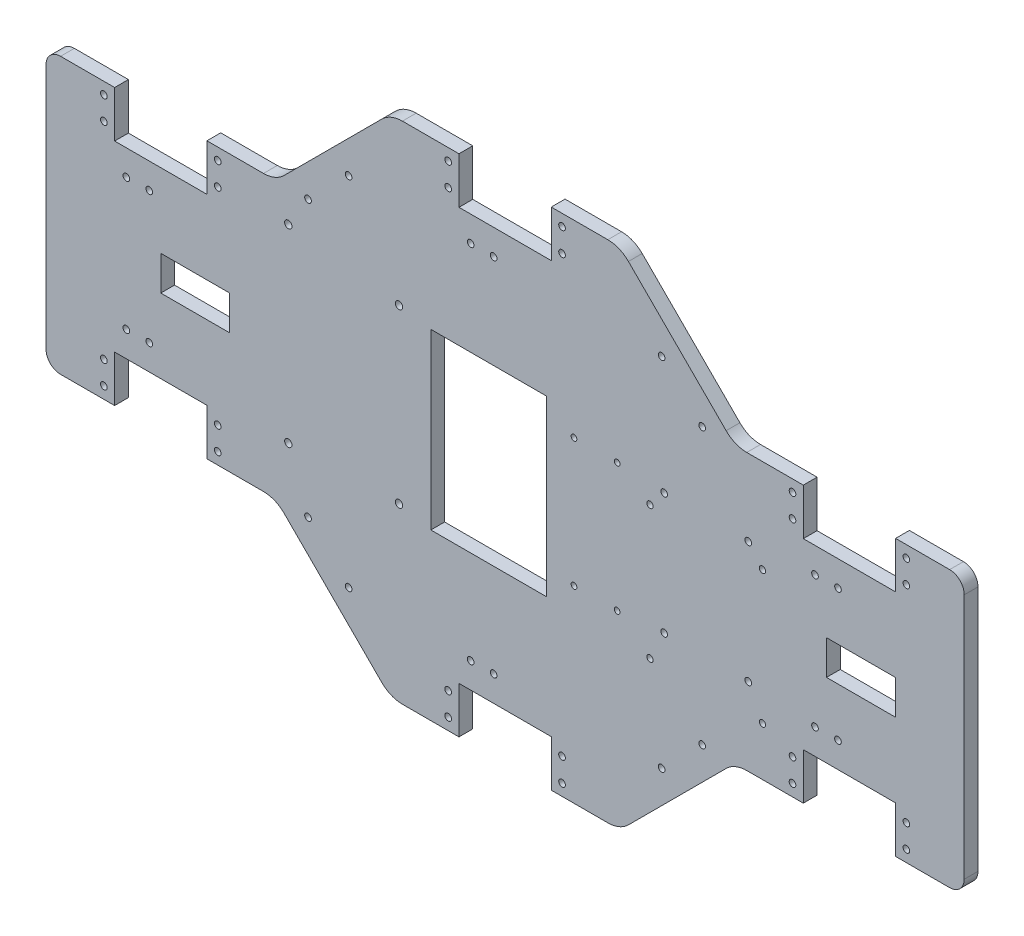
SolidWorks part; units mm, degrees
ref_plane "Front" through (0, 0, 0) normal (0, 0, 1) x (1, 0, 0)
ref_plane "Top" through (0, 0, 0) normal (0, 1, 0) x (1, 0, 0)
ref_plane "Right" through (0, 0, 0) normal (1, 0, 0) x (0, 0, -1)
sketch "Esquisse1" plane through (0, 0, 0) normal (0, 0, 1) x (1, 0, 0)
  line L0 (100, -60) -> (150, -110)
  line L1 (0, 0) -> (25.8386, 0)
  line L2 (0, 0) -> (0, -60)
  line L3 (0, -60) -> (100, -60)
  line L5 (0, 0) -> (100, -60) construction
  line L6 (0, -60) -> (25.8386, 0) construction
  line L7 (150, -110) -> (250, -110)
  line L8 (250, -110) -> (300, -60)
  line L9 (300, -60) -> (400, -60)
  line L10 (400, -60) -> (400, 0)
  line L11 (400, 0) -> (25.8386, 0)
  point P0 (0, 0)
  dimension "D1" = 100
  dimension "D2" = 100
  dimension "D3" = 100
  dimension "D4" = 135
  dimension "D5" = 135
  dimension "D6" = 0
  dimension "D7" = 50
  dimension "D8" = 60
extrude "Boss.-Extru.1" add sketch "Esquisse1" along normal blind 6
sketch "Esquisse2" plane through (0, 0, 6) normal (0, 0, 1) x (1, 0, 0)
  line L0 (0, -60) -> (100, -60) construction
  line L1 (29.9, -39.8) -> (70.1, -39.8)
  line L2 (29.9, -39.8) -> (29.9, -60)
  line L3 (29.9, -60) -> (70.1, -60)
  line L4 (70.1, -39.8) -> (70.1, -60)
  line L5 (29.9, -39.8) -> (70.1, -60) construction
  line L6 (29.9, -60) -> (70.1, -39.8) construction
  line L7 (0, 0) -> (0, -60) construction
  point P0 (0, -90)
  dimension "D1" = 20.2
  dimension "D2" = 40.2
  dimension "D3" = 29.9
extrude "Enlèv. mat.-Extru.1" cut sketch "Esquisse2" against normal up to next
sketch "Esquisse3" plane through (0, 0, 6) normal (0, 0, 1) x (1, 0, 0)
  line L0 (29.9, -49.9) -> (70.1, -49.9) construction
  line L1 (29.9, -39.8) -> (29.9, -60) construction
  line L2 (70.1, -60) -> (70.1, -39.8) construction
  circle A0 centre (25.2, -54.9) radius 1.45
  circle A1 centre (74.8, -54.9) radius 1.45
  circle A2 centre (74.8, -44.9) radius 1.45
  circle A3 centre (25.2, -44.9) radius 1.45
  circle A4 centre (35, -28.7) radius 1.45
  circle A5 centre (45, -28.7) radius 1.45
  dimension "D1" = 4.7
  dimension "D2" = 5
  dimension "D3" = 49.6
  dimension "D4" = 2.9
  dimension "D5" = 4.7
  dimension "D6" = 2.9
  dimension "D7" = 2.9
  dimension "D8" = 10
  dimension "D9" = 9.8
  dimension "D10" = 16.2
  dimension "D11" = 0
extrude "Enlèv. mat.-Extru.2" cut sketch "Esquisse3" against normal up to next
sketch "Sketch2" plane through (0, 0, 0) normal (0, 0, 1) x (1, 0, 0)
  line L0 (150, -110) -> (250, -110) construction
  line L1 (329.9, -39.8) -> (370.1, -39.8)
  line L2 (329.9, -39.8) -> (329.9, -60)
  line L3 (329.9, -60) -> (370.1, -60)
  line L4 (370.1, -39.8) -> (370.1, -60)
  line L5 (329.9, -39.8) -> (370.1, -60) construction
  line L6 (329.9, -60) -> (370.1, -39.8) construction
  line L7 (300, -60) -> (400, -60) construction
  line L8 (400, -60) -> (400, 0) construction
  line L9 (179.9, -89.8) -> (220.1, -89.8)
  line L10 (179.9, -89.8) -> (179.9, -110)
  line L11 (179.9, -110) -> (220.1, -110)
  line L12 (220.1, -89.8) -> (220.1, -110)
  line L13 (179.9, -89.8) -> (220.1, -110) construction
  line L14 (179.9, -110) -> (220.1, -89.8) construction
  point P0 (0, -90)
  point P11 (-35, 0)
  dimension "D1" = 20.2
  dimension "D2" = 40.2
  dimension "D3" = 29.9
  dimension "D4" = 40.2
  dimension "D5" = 20.2
  dimension "D6" = 29.9
extrude "Cut-Extrude2" cut sketch "Sketch2" against normal through all and the other way through all
sketch "Sketch5" plane through (0, 0, 0) normal (0, 0, 1) x (1, 0, 0)
  line L0 (180, -99.9) -> (220.1, -99.9) construction
  line L1 (220.1, -110) -> (220.1, -89.8) construction
  line L2 (329.9, -49.9) -> (370.1, -49.9) construction
  line L4 (370.1, -60) -> (370.1, -39.8) construction
  line L5 (329.9, -39.8) -> (329.9, -60) construction
  circle A0 centre (175.2001, -104.9) radius 1.45
  circle A1 centre (224.8, -104.98) radius 1.45
  circle A2 centre (224.8, -94.82) radius 1.45
  circle A3 centre (175.2001, -94.9) radius 1.45
  circle A4 centre (325.2, -54.9) radius 1.45
  circle A5 centre (374.8, -54.9) radius 1.45
  circle A6 centre (374.8, -44.9) radius 1.45
  circle A7 centre (325.2, -44.9) radius 1.45
  circle A8 centre (185.0001, -78.7) radius 1.45
  circle A9 centre (195.0001, -78.7) radius 1.45
  circle A10 centre (335, -28.7) radius 1.45
  circle A11 centre (345, -28.7) radius 1.45
  dimension "D1" = 5.08
  dimension "D2" = 5
  dimension "D3" = 49.6
  dimension "D4" = 2.9
  dimension "D5" = 4.7
  dimension "D10" = 2.9
  dimension "D11" = 2.9
  dimension "D12" = 2.9
  dimension "D16" = 2.9
  dimension "D17" = 2.9
  dimension "D6" = 5
  dimension "D7" = 5
  dimension "D8" = 4.7
  dimension "D9" = 4.7
  dimension "D13" = 10
  dimension "D14" = 9.8
  dimension "D15" = 16.2
  dimension "D18" = 9.8
  dimension "D19" = 16.2
  dimension "D20" = 10
  dimension "D21" = 0
  dimension "D22" = 0
extrude "Cut-Extrude4" cut sketch "Sketch5" along normal through all
mirror "Mirror1" about plane through (0, 0, 0) normal (0, 1, 0) of "Cut-Extrude4", "Cut-Extrude2", "Enlèv. mat.-Extru.1", "Enlèv. mat.-Extru.2", "Boss.-Extru.1"
sketch "Esquisse4" plane through (0, 0, 6) normal (0, 0, 1) x (1, 0, 0)
  circle A0 centre (263.1, -38.8) radius 1.375
  circle A4 centre (312.1, -38.8) radius 1.375
  circle A5 centre (312.1, 19.2) radius 1.375
  circle A6 centre (263.1, 19.2) radius 1.375
  dimension "D1" = 2.75
  dimension "D2" = 2
  dimension "D3" = 43
  dimension "D4" = 51
  dimension "D5" = 2
extrude "Enlèv. mat.-Extru.4" cut sketch "Esquisse4" against normal through all
sketch "Esquisse6" plane through (0, 0, 0) normal (0, 0, -1) x (-1, 0, 0)
  circle A0 centre (-269.29, -26.11) radius 1.45
  circle A4 centre (-305.92, -26.11) radius 1.45
  circle A5 centre (-305.92, 26.72) radius 1.45
  circle A6 centre (-269.29, 26.72) radius 1.45
  dimension "D1" = 2.9
  dimension "D2" = 2
  dimension "D3" = 63.69
  dimension "D4" = 49.19
  dimension "D5" = 2
extrude "Enlèv. mat.-Extru.6" cut sketch "Esquisse6" against normal through all
sketch "Esquisse8" plane through (0, 0, 0) normal (0, 0, -1) x (-1, 0, 0)
  circle A0 centre (-230, 27.95) radius 1.25
  circle A1 centre (-248.8, 27.95) radius 1.25
  circle A2 centre (-248.8, -27.95) radius 1.25
  circle A3 centre (-230, -27.95) radius 1.25
  dimension "D1" = 2.5
  dimension "D2" = 70
  dimension "D3" = 32.05
  dimension "D4" = 2
  dimension "D5" = 2
extrude "Enlèv. mat.-Extru.7" cut sketch "Esquisse8" against normal through all
sketch "Esquisse9" plane through (0, 0, 0) normal (0, 0, -1) x (-1, 0, 0)
  circle A1 centre (-153.759, -35.08) radius 1.6
  circle A2 centre (-105.539, -36.31) radius 1.6
  circle A3 centre (-105.539, 46.16) radius 1.6
  circle A4 centre (-153.759, 39.8) radius 1.6
  dimension "D8" = 1.23
  dimension "D1" = 74.88
  dimension "D2" = 82.47
  dimension "D3" = 48.22
  dimension "D4" = 48.22
  dimension "D5" = 48.22
  dimension "D6" = 26.141
  dimension "D7" = 50
extrude "Enlèv. mat.-Extru.8" cut sketch "Esquisse9" against normal through all
sketch "Esquisse10" plane through (0, 0, 0) normal (0, 0, -1) x (-1, 0, 0)
  line L0 (-218.1, -38.05) -> (-218.1, 37.64)
  line L1 (-218.1, 37.64) -> (-167.65, 37.64)
  line L2 (-167.65, 37.64) -> (-167.65, -38.05)
  line L3 (-167.65, -38.05) -> (-218.1, -38.05)
  dimension "D1" = 50.45
  dimension "D2" = 75.69
  dimension "D3" = 2
  dimension "D4" = 52.16
extrude "Enlèv. mat.-Extru.9" cut sketch "Esquisse10" against normal through all
sketch "Esquisse11" plane through (0, 0, 0) normal (0, 0, -1) x (-1, 0, 0)
  line L1 (-340, 7.5) -> (-370, 7.5)
  line L2 (-340, 7.5) -> (-340, -7.5)
  line L3 (-340, -7.5) -> (-370, -7.5)
  line L4 (-370, 7.5) -> (-370, -7.5)
  line L5 (-50, 7.5) -> (-80, 7.5)
  line L6 (-50, 7.5) -> (-50, -7.5)
  line L7 (-50, -7.5) -> (-80, -7.5)
  line L8 (-80, 7.5) -> (-80, -7.5)
  dimension "D1" = 30
  dimension "D2" = 30
  dimension "D3" = 30
  dimension "D4" = 50
  dimension "D5" = 15
  dimension "D6" = 15
  dimension "D7" = 52.5
  dimension "D8" = 52.5
extrude "Enlèv. mat.-Extru.10" cut sketch "Esquisse11" against normal through all
ref_plane "Plan1" through (200, 0, 0) normal (-1, 0, 0) x (0, 0, 1)
ref_plane "Plan2" through (0, 0, 0) normal (0, 1, 0) x (1, 0, 0)
sketch "Esquisse12" plane through (0, 0, 6) normal (0, 0, 1) x (1, 0, 0)
  line L1 (200, 24.0954) -> (200, -24.0954) construction
  line L2 (22.5792, 0) -> (-22.5792, 0) construction
  line L3 (100, 60) -> (150, 110) construction
  circle A0 centre (131.8198, 77.6777) radius 1.45
  circle A1 centre (114.1421, 60) radius 1.45
  circle A2 centre (285.8579, 60) radius 1.45
  circle A3 centre (268.1802, 77.6777) radius 1.45
  circle A4 centre (285.8579, -60) radius 1.45
  circle A5 centre (268.1802, -77.6777) radius 1.45
  circle A6 centre (131.8198, -77.6777) radius 1.45
  circle A7 centre (114.1421, -60) radius 1.45
  dimension "D1" = 2.9
  dimension "D2" = 2.9
  dimension "D3" = 25
  dimension "D4" = 10
  dimension "D5" = 14.1421
  dimension "D6" = 0
extrude "Enlèv. mat.-Extru.11" cut sketch "Esquisse12" against normal through all
fillet "Fillet1" radius 6.35 4 edges at (400, 60, 3) (400, -60, 3) (0, -60, 3) (0, 60, 3)
fillet "Fillet2" radius 12.7 8 edges at (150, -110, 3) (100, -60, 3) (250, -110, 3) (300, -60, 3) (300, 60, 3) (250, 110, 3) (150, 110, 3) (100, 60, 3)
